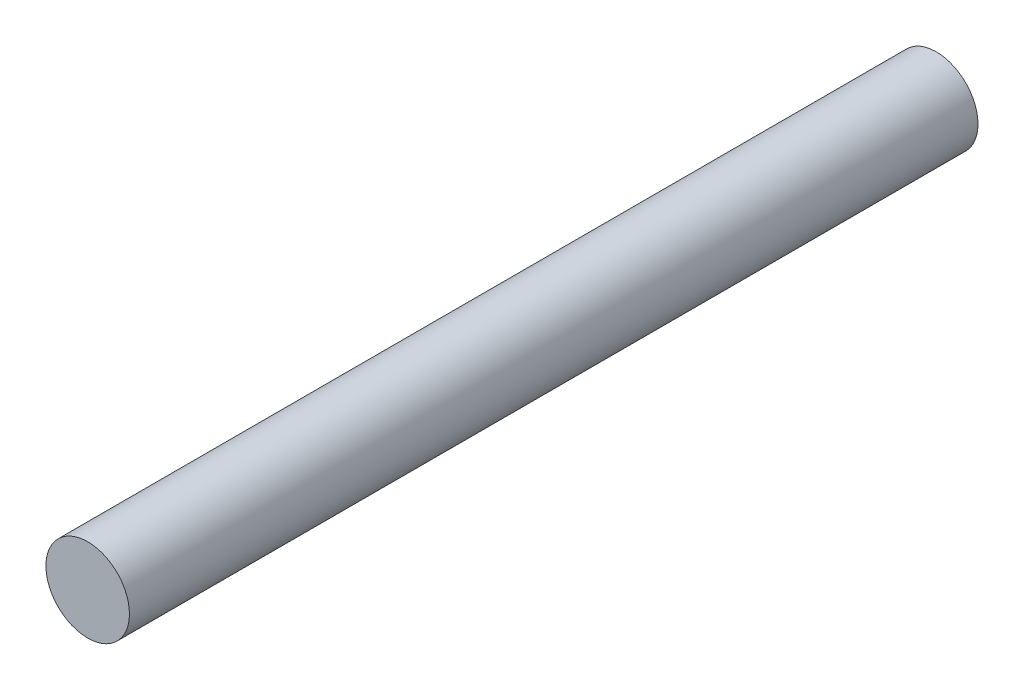
SolidWorks part; units mm, degrees
ref_plane "Front Plane" through (0, 0, 0) normal (0, 0, 1) x (1, 0, 0)
ref_plane "Top Plane" through (0, 0, 0) normal (0, 1, 0) x (1, 0, 0)
ref_plane "Right Plane" through (0, 0, 0) normal (1, 0, 0) x (0, 0, -1)
sketch "Sketch1" plane through (0, 0, 0) normal (0, 0, 1) x (1, 0, 0)
  circle A0 centre (0, 0) radius 1.25
  dimension "D1" = 2.5
extrude "Boss-Extrude1" add sketch "Sketch1" along normal blind 25.4
